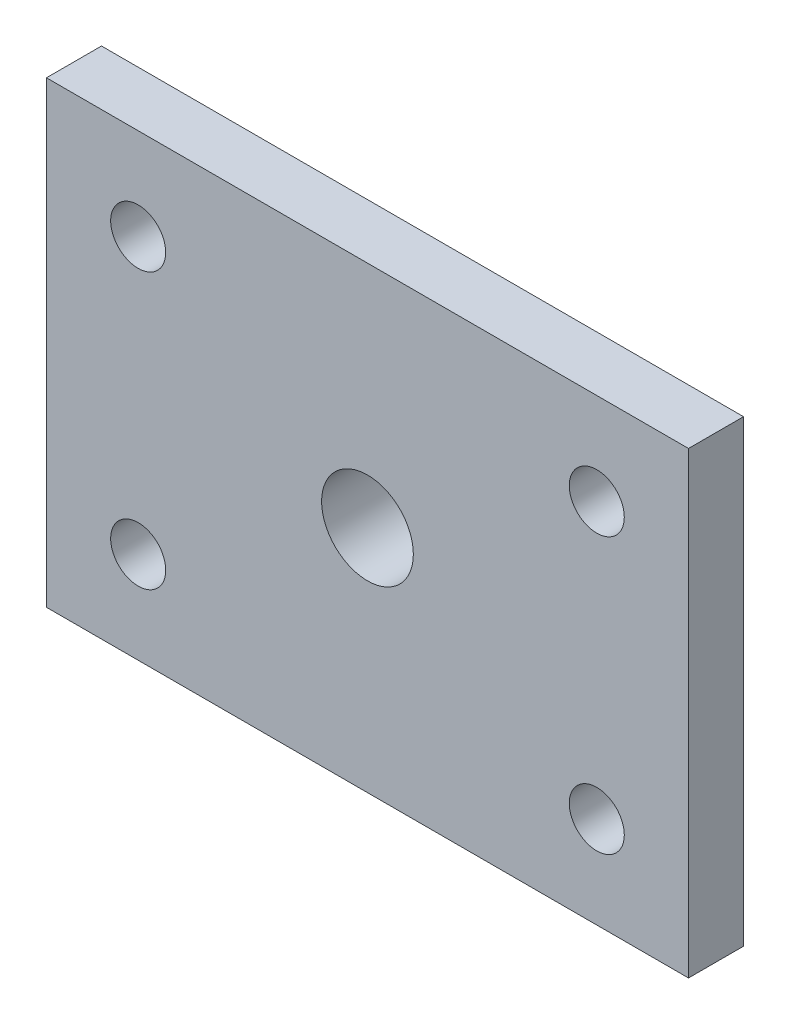
SolidWorks part; units mm, degrees
material "6061 Alloy"
ref_plane "Front Plane" through (0, 0, 0) normal (0, 0, 1) x (1, 0, 0)
ref_plane "Top Plane" through (0, 0, 0) normal (0, 1, 0) x (1, 0, 0)
ref_plane "Right Plane" through (0, 0, 0) normal (1, 0, 0) x (0, 0, -1)
sketch "Sketch1" plane through (0, 0, 0) normal (0, 0, 1) x (1, 0, 0)
  line L1 (-17.5, 12.5) -> (17.5, 12.5)
  line L2 (-17.5, 12.5) -> (-17.5, -12.5)
  line L3 (-17.5, -12.5) -> (17.5, -12.5)
  line L4 (17.5, 12.5) -> (17.5, -12.5)
  line L5 (-17.5, 12.5) -> (17.5, -12.5) construction
  line L6 (-17.5, -12.5) -> (17.5, 12.5) construction
  point P0 (0, 0)
  dimension "D1" = 35
  dimension "D2" = 25
extrude "Boss-Extrude1" add sketch "Sketch1" along normal blind 3
sketch "Sketch2" plane through (0, 0, 3) normal (0, 0, 1) x (1, 0, 0)
  line L0 (-17.5, 12.5) -> (-17.5, -12.5) construction
  line L1 (-12.5, 7.5) -> (12.5, 7.5) construction
  line L2 (-12.5, 7.5) -> (-12.5, -7.5) construction
  line L3 (-12.5, -7.5) -> (12.5, -7.5) construction
  line L4 (12.5, 7.5) -> (12.5, -7.5) construction
  line L5 (-12.5, 7.5) -> (12.5, -7.5) construction
  line L6 (-12.5, -7.5) -> (12.5, 7.5) construction
  line L7 (17.5, 12.5) -> (-17.5, 12.5) construction
  circle A0 centre (0, 0) radius 2.5
  circle A1 centre (-12.5, 7.5) radius 1.5
  circle A2 centre (12.5, 7.5) radius 1.5
  circle A3 centre (12.5, -7.5) radius 1.5
  circle A4 centre (-12.5, -7.5) radius 1.5
  dimension "D1" = 3
  dimension "D2" = 5
  dimension "D3" = 5
  dimension "D4" = 5
extrude "Cut-Extrude1" cut sketch "Sketch2" against normal blind 3
sketch "Sketch3" plane through (0, 0, 0) normal (0, 0, -1) x (-1, 0, 0)
  circle A0 centre (0, 0) radius 2.5
  circle A1 centre (0, 0) radius 7.5
  dimension "D1" = 5
  dimension "D2" = 15
extrude "Boss-Extrude2" add sketch "Sketch3" along normal blind 5
